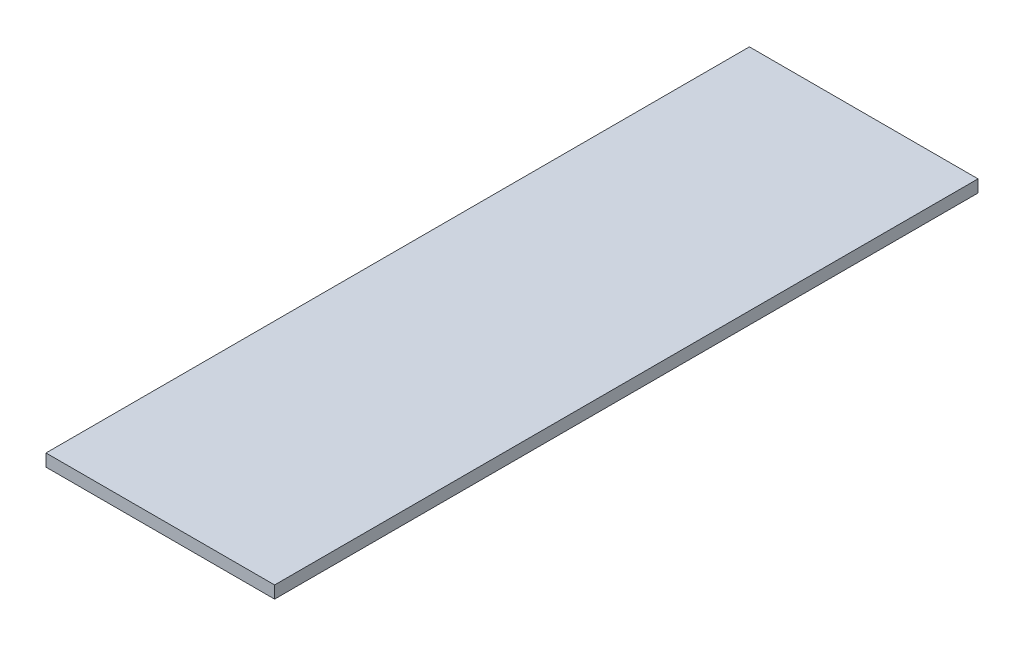
SolidWorks part; units mm, degrees
ref_plane "Front Plane" through (0, 0, 0) normal (0, 0, 1) x (1, 0, 0)
ref_plane "Top Plane" through (0, 0, 0) normal (0, 1, 0) x (1, 0, 0)
ref_plane "Right Plane" through (0, 0, 0) normal (1, 0, 0) x (0, 0, -1)
sketch "Sketch1" plane through (0, 0, 0) normal (0, 1, 0) x (1, 0, 0)
  line L1 (-6.5, -20) -> (6.5, -20)
  line L2 (-6.5, -20) -> (-6.5, 20)
  line L3 (-6.5, 20) -> (6.5, 20)
  line L4 (6.5, -20) -> (6.5, 20)
  line L5 (-6.5, -20) -> (6.5, 20) construction
  line L6 (-6.5, 20) -> (6.5, -20) construction
  point P0 (0, 0)
  dimension "D1" = 40
  dimension "D2" = 13
extrude "Boss-Extrude1" add sketch "Sketch1" along normal blind 0.7
